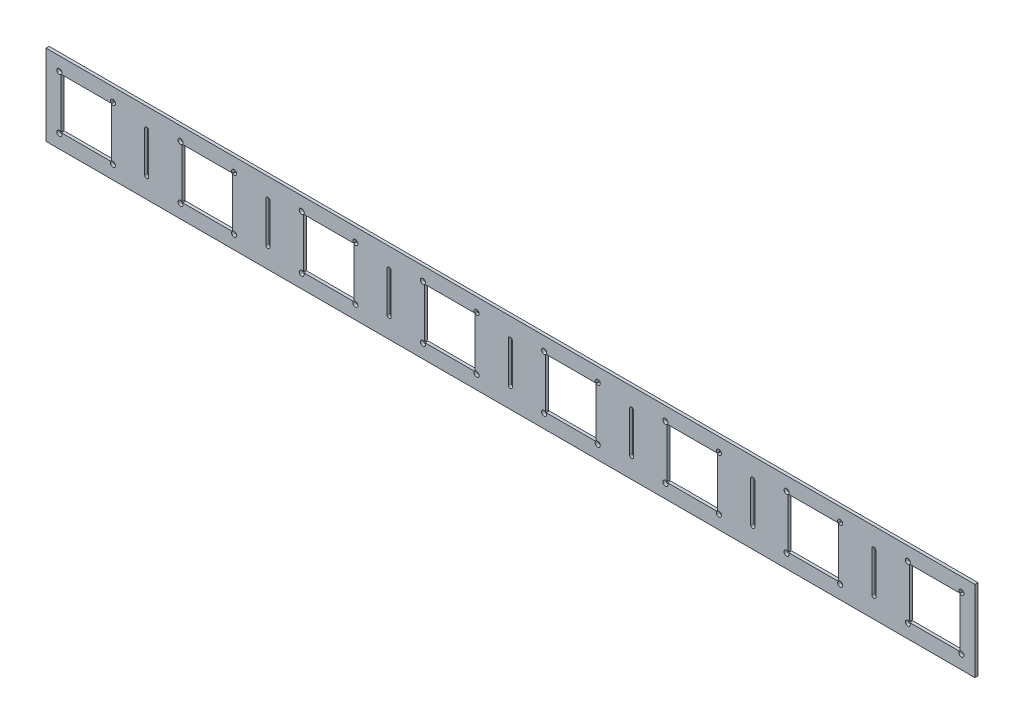
SolidWorks part; units mm, degrees
ref_plane "Front" through (0, 0, 0) normal (0, 0, 1) x (1, 0, 0)
ref_plane "Top" through (0, 0, 0) normal (0, 1, 0) x (1, 0, 0)
ref_plane "Right" through (0, 0, 0) normal (1, 0, 0) x (0, 0, -1)
sketch "Эскиз1" plane through (0, 0, 0) normal (0, 0, 1) x (1, 0, 0)
  line L0 (-993.2308, 40) -> (49006.7692, 40) construction
  line L1 (40, -989.4981) -> (40, 49010.5019) construction
  line L2 (-989.3345, -40) -> (49010.6655, -40) construction
  line L3 (23, 25) -> (-23, 25) construction
  line L6 (25, -23) -> (25, 23) construction
  line L7 (-23, -25) -> (23, -25) construction
  line L8 (-880, -1002.1952) -> (-880, 48997.8048) construction
  line L9 (-865, 23) -> (-865, -23) construction
  line L10 (-145, -25) -> (-95, -25)
  line L11 (-879.7251, 40) -> (40, 40)
  line L12 (-879.7251, 40) -> (-879.7251, -40)
  line L13 (-879.7251, -40) -> (40, -40)
  line L14 (40, 40) -> (40, -40)
  line L15 (-25, -25) -> (25, -25)
  line L16 (-25, -25) -> (-25, 25)
  line L17 (-25, 25) -> (25, 25)
  line L18 (25, -25) -> (25, 25)
  line L19 (-25, -25) -> (25, 25) construction
  line L20 (-25, 25) -> (25, -25) construction
  line L21 (-95, -25) -> (-95, 25)
  line L22 (-145, 25) -> (-95, 25)
  line L23 (-145, -25) -> (-145, 25)
  line L24 (-265, -25) -> (-215, -25)
  line L25 (-215, -25) -> (-215, 25)
  line L26 (-265, 25) -> (-215, 25)
  line L27 (-265, -25) -> (-265, 25)
  line L28 (-385, -25) -> (-335, -25)
  line L29 (-335, -25) -> (-335, 25)
  line L30 (-385, 25) -> (-335, 25)
  line L31 (-385, -25) -> (-385, 25)
  line L32 (-505, -25) -> (-455, -25)
  line L33 (-455, -25) -> (-455, 25)
  line L34 (-505, 25) -> (-455, 25)
  line L35 (-505, -25) -> (-505, 25)
  line L36 (-625, -25) -> (-575, -25)
  line L37 (-575, -25) -> (-575, 25)
  line L38 (-625, 25) -> (-575, 25)
  line L39 (-625, -25) -> (-625, 25)
  line L40 (-745, -25) -> (-695, -25)
  line L41 (-695, -25) -> (-695, 25)
  line L42 (-745, 25) -> (-695, 25)
  line L43 (-745, -25) -> (-745, 25)
  line L44 (-865, -25) -> (-815, -25)
  line L45 (-815, -25) -> (-815, 25)
  line L46 (-865, 25) -> (-815, 25)
  line L47 (-865, -25) -> (-865, 25)
  circle A0 centre (26.5165, -26.5165) radius 2.5
  circle A1 centre (26.5165, 26.5165) radius 2.5
  circle A2 centre (-26.5165, -26.5165) radius 2.5
  circle A3 centre (-26.5165, 26.5165) radius 2.5
  circle A4 centre (-146.5165, 26.5165) radius 2.5
  circle A5 centre (-93.4835, 26.5165) radius 2.5
  circle A6 centre (-146.5165, -26.5165) radius 2.5
  circle A7 centre (-93.4835, -26.5165) radius 2.5
  circle A8 centre (-266.5165, 26.5165) radius 2.5
  circle A9 centre (-213.4835, 26.5165) radius 2.5
  circle A10 centre (-266.5165, -26.5165) radius 2.5
  circle A11 centre (-213.4835, -26.5165) radius 2.5
  circle A12 centre (-386.5165, 26.5165) radius 2.5
  circle A13 centre (-333.4835, 26.5165) radius 2.5
  circle A14 centre (-386.5165, -26.5165) radius 2.5
  circle A15 centre (-333.4835, -26.5165) radius 2.5
  circle A16 centre (-506.5165, 26.5165) radius 2.5
  circle A17 centre (-453.4835, 26.5165) radius 2.5
  circle A18 centre (-506.5165, -26.5165) radius 2.5
  circle A19 centre (-453.4835, -26.5165) radius 2.5
  circle A20 centre (-626.5165, 26.5165) radius 2.5
  circle A21 centre (-573.4835, 26.5165) radius 2.5
  circle A22 centre (-626.5165, -26.5165) radius 2.5
  circle A23 centre (-573.4835, -26.5165) radius 2.5
  circle A24 centre (-746.5165, 26.5165) radius 2.5
  circle A25 centre (-693.4835, 26.5165) radius 2.5
  circle A26 centre (-746.5165, -26.5165) radius 2.5
  circle A27 centre (-693.4835, -26.5165) radius 2.5
  circle A28 centre (-866.5165, 26.5165) radius 2.5
  circle A29 centre (-813.4835, 26.5165) radius 2.5
  circle A30 centre (-866.5165, -26.5165) radius 2.5
  circle A31 centre (-813.4835, -26.5165) radius 2.5
  point P32 (0, 0)
  dimension "D1" = 15
  dimension "D2" = 15
  dimension "D3" = 15
  dimension "D4" = 15
  dimension "D6" = 50
  dimension "D7" = 50
  dimension "D5" = 8
  dimension "D8" = 8
extrude "Бобышка-Вытянуть1" add sketch "Эскиз1" along normal blind 3 contours L14 L11 L12 L13 A31 L44 A30 L47 A28 L46 A29 L45 A27 L40 A26 L43 A24 L42 A25 L41 A23 L36 A22 L39 A20 L38 A21 L37 A19 L32 A18 L35 A16 L34 A17 L33 A15 L28 A14 L31 A12 L30 A13 L29 A11
sketch "Эскиз2" plane through (0, 0, 0) normal (0, 0, -1) x (-1, 0, 0)
  line L0 (60, -997.2973) -> (60, 49002.7027) construction
  line L1 (60, 20) -> (60, -20) construction
  line L2 (62, 20) -> (62, -20)
  line L3 (58, 20) -> (58, -20)
  line L4 (180, 20) -> (180, -20) construction
  line L5 (182, 20) -> (182, -20)
  line L6 (178, 20) -> (178, -20)
  line L7 (300, 20) -> (300, -20) construction
  line L8 (302, 20) -> (302, -20)
  line L9 (298, 20) -> (298, -20)
  line L10 (420, 20) -> (420, -20) construction
  line L11 (422, 20) -> (422, -20)
  line L12 (418, 20) -> (418, -20)
  line L13 (540, 20) -> (540, -20) construction
  line L14 (542, 20) -> (542, -20)
  line L15 (538, 20) -> (538, -20)
  line L16 (660, 20) -> (660, -20) construction
  line L17 (662, 20) -> (662, -20)
  line L18 (658, 20) -> (658, -20)
  line L19 (780, 20) -> (780, -20) construction
  line L20 (782, 20) -> (782, -20)
  line L21 (778, 20) -> (778, -20)
  arc A0 (62, 20) -> (58, 20) centre (60, 20) ccw
  arc A1 (58, -20) -> (62, -20) centre (60, -20) ccw
  arc A2 (182, 20) -> (178, 20) centre (180, 20) ccw
  arc A3 (178, -20) -> (182, -20) centre (180, -20) ccw
  arc A4 (302, 20) -> (298, 20) centre (300, 20) ccw
  arc A5 (298, -20) -> (302, -20) centre (300, -20) ccw
  arc A6 (422, 20) -> (418, 20) centre (420, 20) ccw
  arc A7 (418, -20) -> (422, -20) centre (420, -20) ccw
  arc A8 (542, 20) -> (538, 20) centre (540, 20) ccw
  arc A9 (538, -20) -> (542, -20) centre (540, -20) ccw
  arc A10 (662, 20) -> (658, 20) centre (660, 20) ccw
  arc A11 (658, -20) -> (662, -20) centre (660, -20) ccw
  arc A12 (782, 20) -> (778, 20) centre (780, 20) ccw
  arc A13 (778, -20) -> (782, -20) centre (780, -20) ccw
  point P5 (60, 0)
  point P14 (180, 0)
  point P21 (300, 0)
  point P28 (420, 0)
  point P35 (540, 0)
  point P42 (660, 0)
  point P49 (780, 0)
  dimension "D3" = 2
  dimension "D1" = 60
  dimension "D2" = 40
  dimension "D4" = 0
  dimension "D5" = 7
extrude "Вырез-Вытянуть1" cut sketch "Эскиз2" against normal blind 3
